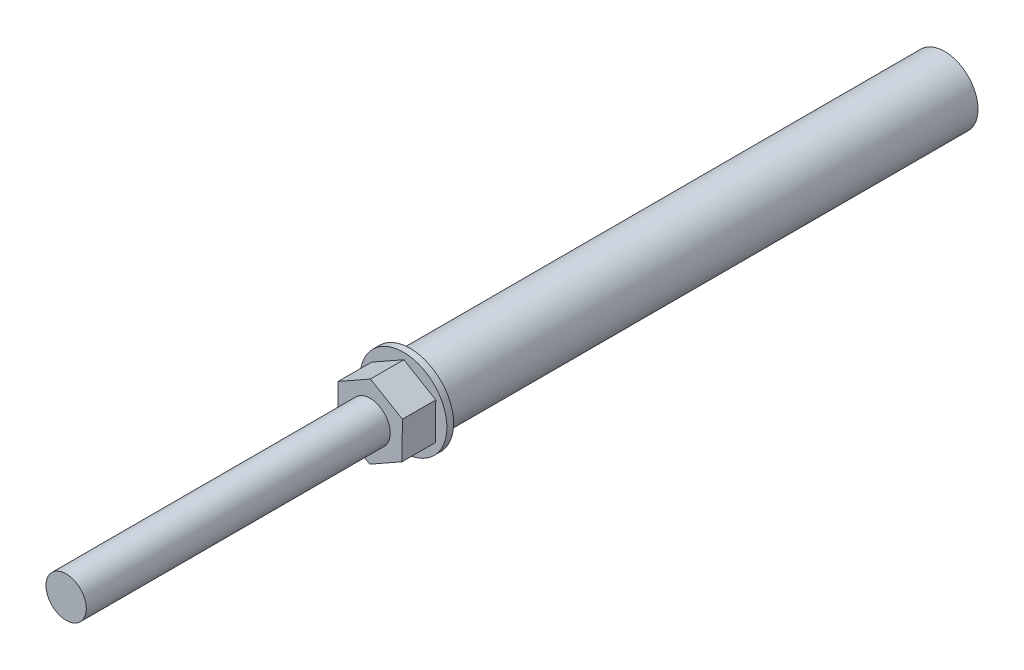
SolidWorks part; units mm, degrees
ref_plane "Front Plane" through (0, 0, 0) normal (0, 0, 1) x (1, 0, 0)
ref_plane "Top Plane" through (0, 0, 0) normal (0, 1, 0) x (1, 0, 0)
ref_plane "Right Plane" through (0, 0, 0) normal (1, 0, 0) x (0, 0, -1)
sketch "Sketch1" plane through (0, 0, 0) normal (0, 0, 1) x (1, 0, 0)
  circle A0 centre (0, 0) radius 5
  dimension "D1" = 10
extrude "Boss-Extrude1" add sketch "Sketch1" along normal blind 80
sketch "Sketch2" plane through (0, 0, 80) normal (0, 0, 1) x (1, 0, 0)
  circle A0 centre (0, 0) radius 6.5
  dimension "D1" = 13
extrude "Boss-Extrude2" add sketch "Sketch2" along normal blind 1
sketch "Sketch5" plane through (0, 0, 81) normal (0, 0, 1) x (1, 0, 0)
  line L1 (4.7789, -2.8202) -> (4.8318, 2.7285)
  line L2 (4.8318, 2.7285) -> (0.0529, 5.5487)
  line L3 (0.0529, 5.5487) -> (-4.7789, 2.8202)
  line L4 (-4.7789, 2.8202) -> (-4.8318, -2.7285)
  line L5 (-4.8318, -2.7285) -> (-0.0529, -5.5487)
  line L6 (-0.0529, -5.5487) -> (4.7789, -2.8202)
  circle A0 centre (0, 0) radius 4.8055 construction
extrude "Boss-Extrude5" add sketch "Sketch5" along normal blind 5
sketch "Sketch6" plane through (0, 0, 86) normal (0, 0, 1) x (1, 0, 0)
  circle A0 centre (0, 0) radius 3.0197
  dimension "D1" = 6.0393
extrude "Boss-Extrude6" add sketch "Sketch6" along normal blind 45.5
